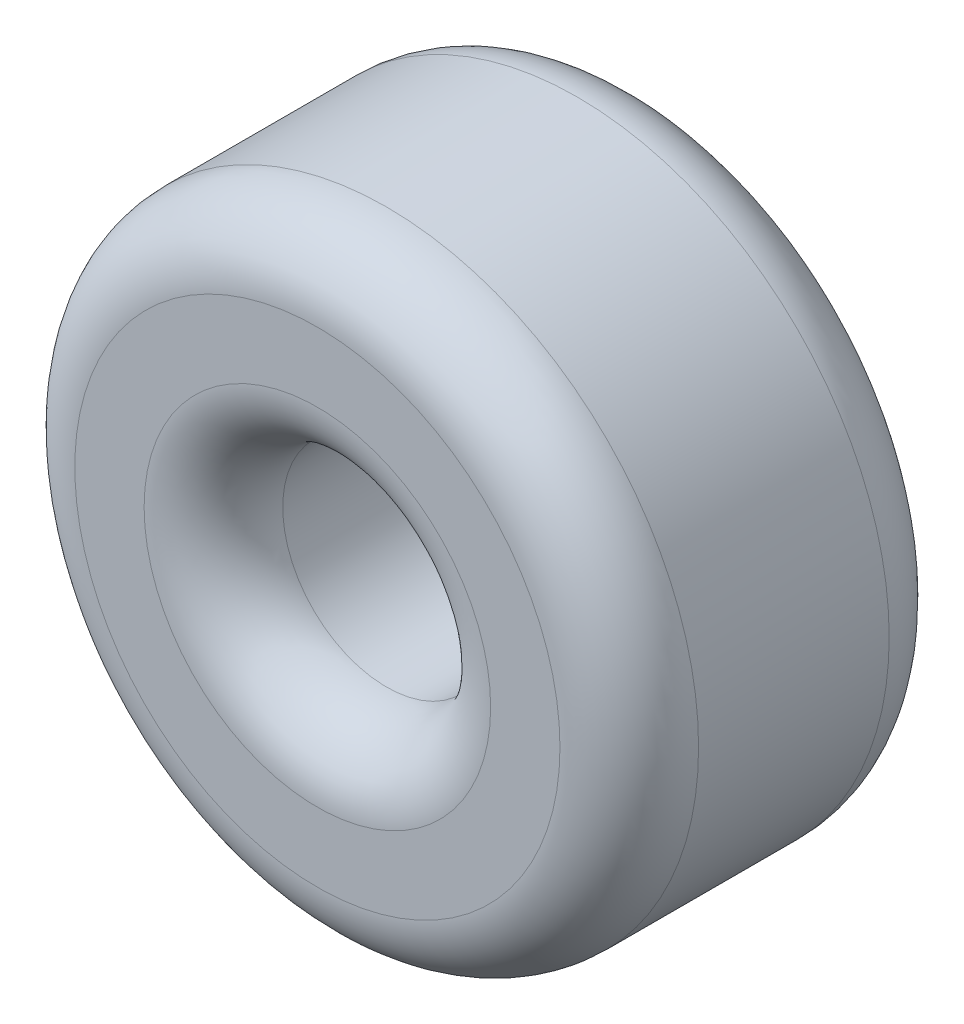
SolidWorks part; units mm, degrees
ref_plane "Front Plane" through (0, 0, 0) normal (0, 0, 1) x (1, 0, 0)
ref_plane "Top Plane" through (0, 0, 0) normal (0, 1, 0) x (1, 0, 0)
ref_plane "Right Plane" through (0, 0, 0) normal (1, 0, 0) x (0, 0, -1)
sketch "Sketch1" plane through (0, 0, 0) normal (0, 0, 1) x (1, 0, 0)
  circle A0 centre (0, 0) radius 9
  circle A1 centre (0, 0) radius 3
  dimension "D1" = 6
  dimension "D2" = 18
extrude "Boss-Extrude1" add sketch "Sketch1" along normal blind 9.5
fillet "Fillet1" radius 2 2 edges at (3, 0, 0) (3, 0, 9.5)
fillet "Fillet2" radius 2 2 edges at (9, 0, 0) (9, 0, 9.5)
scale "Scale1" scale about origin uniform scaling yes scale factor 0.5
